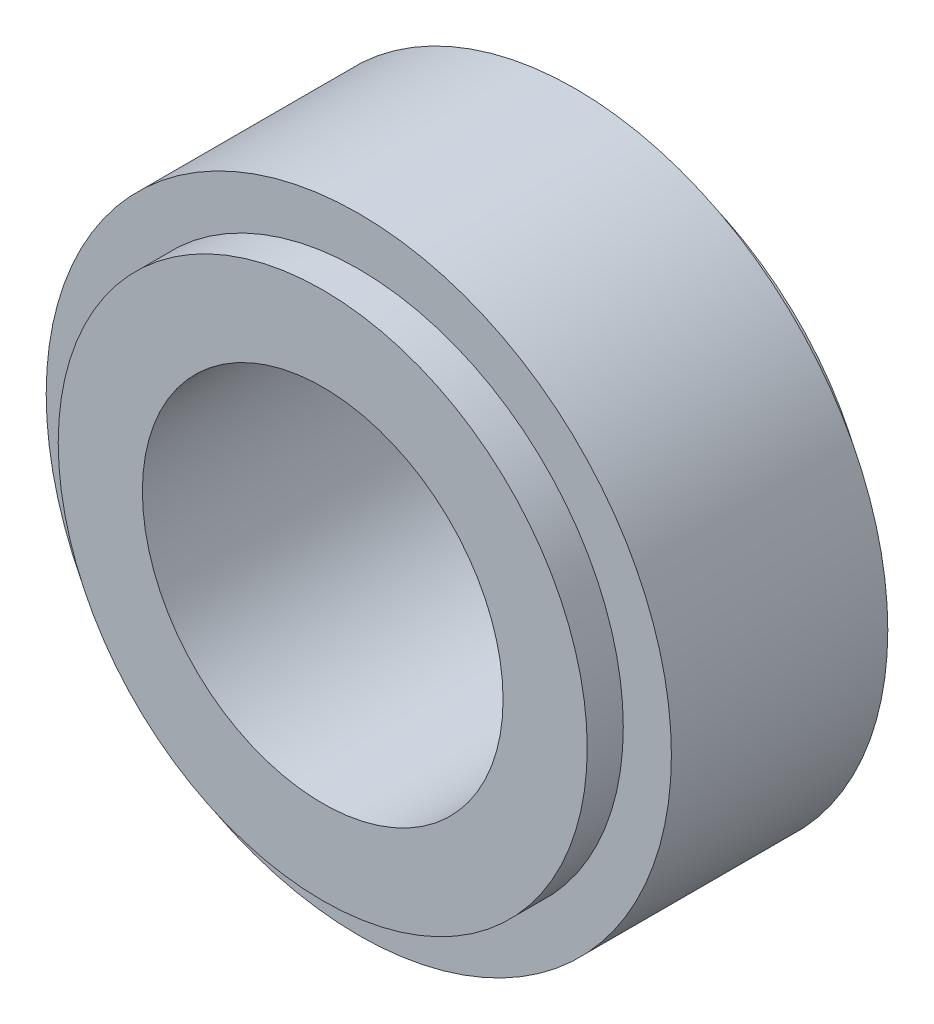
SolidWorks part; units mm, degrees
ref_plane "Front Plane" through (0, 0, 0) normal (0, 0, 1) x (1, 0, 0)
ref_plane "Top Plane" through (0, 0, 0) normal (0, 1, 0) x (1, 0, 0)
ref_plane "Right Plane" through (0, 0, 0) normal (1, 0, 0) x (0, 0, -1)
sketch "Sketch1" plane through (0, 0, 0) normal (0, 0, 1) x (1, 0, 0)
  circle A0 centre (0, 0) radius 7.5
  circle A1 centre (0, 0) radius 11
  dimension "D1" = 22
  dimension "D2" = 15
extrude "Boss-Extrude1" add sketch "Sketch1" along normal mid plane 12
sketch "Sketch2" plane through (0, 0, 0) normal (0, 0, 1) x (1, 0, 0)
  circle A0 centre (0, 0) radius 7.5
  circle A1 centre (0, 0) radius 13
  dimension "D1" = 26
  dimension "D2" = 15
extrude "Boss-Extrude2" add sketch "Sketch2" along normal mid plane 9
